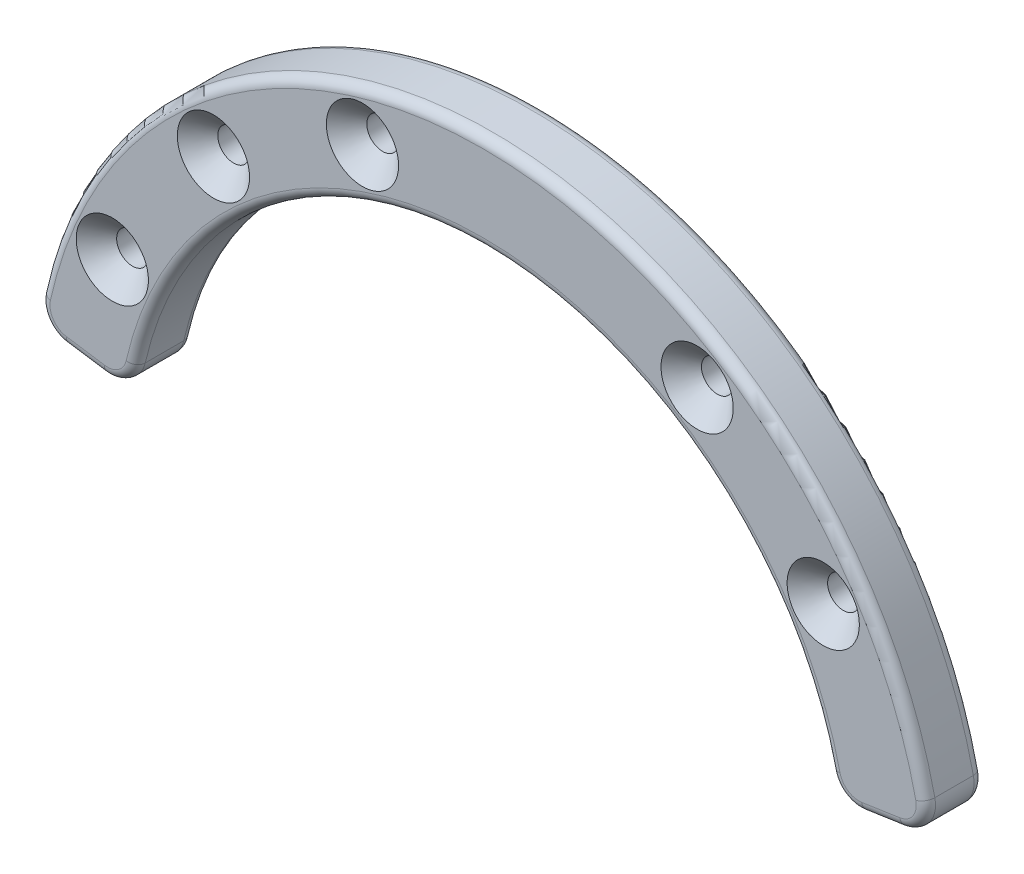
SolidWorks part; units mm, degrees
material "45#"
ref_plane "前视基准面" through (0, 0, 0) normal (0, 0, 1) x (1, 0, 0)
ref_plane "上视基准面" through (0, 0, 0) normal (0, 1, 0) x (1, 0, 0)
ref_plane "右视基准面" through (0, 0, 0) normal (1, 0, 0) x (0, 0, -1)
sketch "草图1" plane through (0, 0, 0) normal (0, 0, 1) x (1, 0, 0)
  line L2 (0, 0) -> (0, 46) construction
  line L8 (-36.5936, 5.4689) -> (-46.4837, 6.947)
  line L10 (36.5936, 5.4689) -> (46.4837, 6.947)
  line L11 (0, 0) -> (-36.5936, 5.4689) construction
  line L12 (0, 0) -> (36.5936, 5.4689) construction
  arc A9 (-45.4947, 6.7992) -> (45.4947, 6.7992) centre (0, 0) ccw construction
  arc A11 (36.5936, 5.4689) -> (-36.5936, 5.4689) centre (0, 0) ccw
  arc A12 (46.4837, 6.947) -> (-46.4837, 6.947) centre (0, 0) ccw
  arc A13 (45.4947, 6.7992) -> (0, 46) centre (0, 0) ccw construction
  circle A14 centre (0, 0) radius 46 construction
  arc A15 (0, 46) -> (-45.4947, 6.7992) centre (0, 0) ccw construction
  arc A16 (-46.4837, 6.947) -> (46.4837, 6.947) centre (0, 0) ccw construction
  circle A17 centre (0, 0) radius 47 construction
  arc A18 (-36.5936, 5.4689) -> (36.5936, 5.4689) centre (0, 0) ccw construction
  circle A19 centre (0, 0) radius 37 construction
  dimension "D1" = 92
  dimension "D2" = 47
  dimension "D3" = 37
  dimension "D4" = 163
extrude "凸台-拉伸1" add sketch "草图1" along normal blind 6
fillet "圆角1" radius 3 4 edges at (36.5936, 5.4689, 3) (46.4837, 6.947, 3) (-46.4837, 6.947, 3) (-36.5936, 5.4689, 3)
hole_wizard "打孔尺寸(%根据)内六角花形半沉头螺钉的类型1" positions "草图8" profile "草图9" countersink size "M6" standard "GB"
sketch "草图8" plane through (0, 0, 6) normal (0, 0, 1) x (1, 0, 0)
  point P0 (-38.4973, 16.7906)
  point P2 (-27.9991, 31.3057)
  point P4 (-12.5269, 40.0884)
  point P6 (22.2222, 35.639)
  point P8 (35.3163, 22.731)
sketch "草图9" plane through (-38.4973, 16.7906, 6) normal (1, 0, 0) x (0, -1, 0)
  line L0 (0, 0) -> (0, 8.4914)
  line L1 (0, 8.4914) -> (1.65, 7.5)
  line L2 (1.65, 7.5) -> (1.65, 2.1)
  line L3 (1.65, 2.1) -> (3.75, 0)
  line L5 (3.75, 0) -> (0, 0)
  line L6 (-1.65, 2.1) -> (-3.75, 0) construction
  line L10 (0, 8.4914) -> (-1.65, 7.5) construction
  line L11 (0, -6.35) -> (0, 107.95) construction
  dimension "孔直径" = 3.3
  dimension "孔深度" = 7.5
  dimension "近端锥形沉头孔直径" = 7.5
  dimension "近端锥形沉头孔角度" = 90
  dimension "导头角度" = 118
fillet "圆角2" radius 1 16 edges at (-37.3131, 6.3859, 0) (-41.4323, 6.1921, 0) (-45.443, 7.7544, 0) (0, 47, 0) (45.443, 7.7544, 0) (41.4323, 6.1921, 0) (37.3131, 6.3859, 0) (-37.3131, 6.3859, 6) (-41.4323, 6.1921, 6) (-45.443, 7.7544, 6) (0, 47, 6) (45.443, 7.7544, 6) (41.4323, 6.1921, 6) (37.3131, 6.3859, 6) (0, 37, 0) (0, 37, 6)
